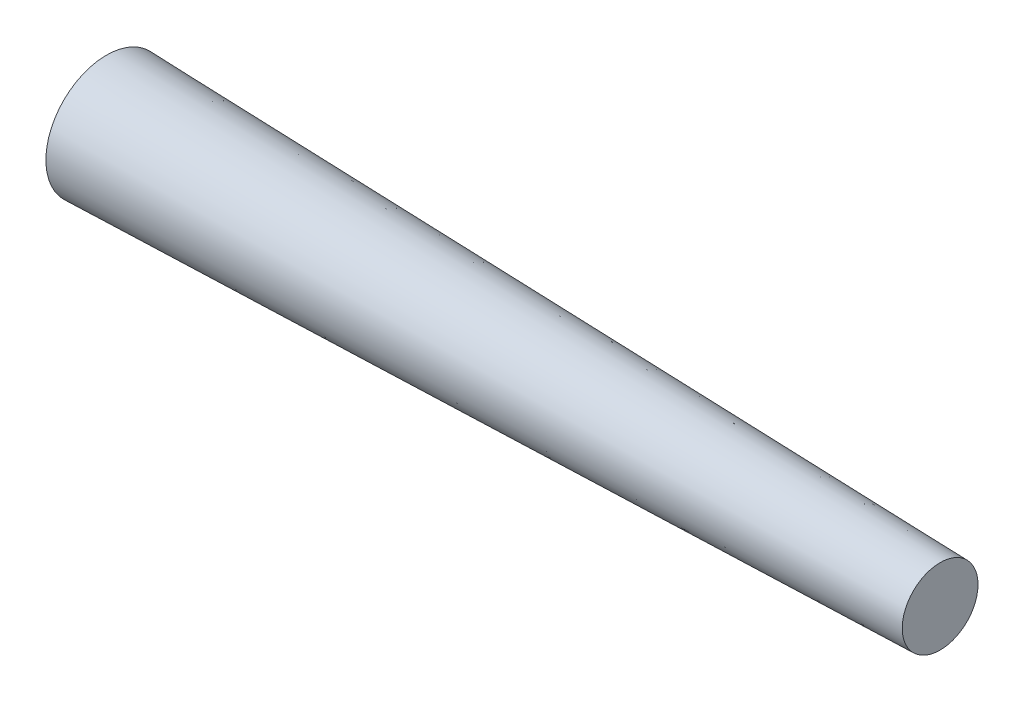
SolidWorks part; units mm, degrees
ref_plane "Front Plane" through (0, 0, 0) normal (0, 0, 1) x (1, 0, 0)
ref_plane "Top Plane" through (0, 0, 0) normal (0, 1, 0) x (1, 0, 0)
ref_plane "Right Plane" through (0, 0, 0) normal (1, 0, 0) x (0, 0, -1)
sketch "Sketch1" plane through (0, 0, 0) normal (0, 0, 1) x (1, 0, 0)
  line L0 (0, 0) -> (-18275.2645, 0) construction
  line L1 (0, 0) -> (0, 8)
  line L2 (0, 8) -> (110, 5)
  line L3 (110, 5) -> (110, 0)
  line L4 (110, 0) -> (0, 0)
  point P5 (0, 0)
  dimension "D1" = 8
  dimension "D2" = 5
  dimension "D3" = 110
revolve "Revolve1" add sketch "Sketch1" angle 360 about L0
